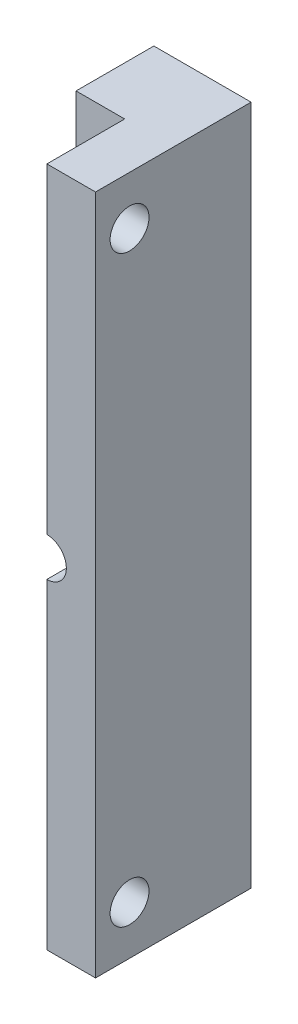
SolidWorks part; units mm, degrees
ref_plane "Front Plane" through (0, 0, 0) normal (0, 0, 1) x (1, 0, 0)
ref_plane "Top Plane" through (0, 0, 0) normal (0, 1, 0) x (1, 0, 0)
ref_plane "Right Plane" through (0, 0, 0) normal (1, 0, 0) x (0, 0, -1)
other "Configuration Table"
sketch "草图1" plane through (0, 0, 0) normal (0, 0, 1) x (1, 0, 0)
  line L0 (-15, 22) -> (-15, -22)
  line L1 (0, 22) -> (15, 22)
  line L2 (0, 22) -> (-15, 22)
  line L3 (15, 22) -> (15, -22)
  line L4 (15, -22) -> (-15, -22)
extrude "凸台-拉伸1" add sketch "草图1" along normal blind 14 contours L0 L4 L3 L1 L2
sketch "草图2" plane through (0, 22, 0) normal (0, 1, 0) x (1, 0, 0)
  line L3 (10, -4) -> (15, -14)
  line L4 (15, -14) -> (-15, -14)
  line L6 (-15, -14) -> (-10, -4)
  line L8 (3.1, -4) -> (3.1, 0)
  line L9 (-15, 0) -> (15, 0) construction
  line L10 (3.1, 0) -> (15, 0)
  line L11 (15, 0) -> (15, -14)
  line L12 (10, -4) -> (3.1, -4)
  line L13 (-3.1, -4) -> (-10, -4)
  line L14 (-15, -14) -> (-15, 0)
  line L15 (-15, 0) -> (-3.1, 0)
  line L16 (-3.1, 0) -> (-3.1, -4)
  line M14 (15, 0) -> (-15, 0)
  line M15 (-15, 0) -> (-15, -14)
  line M17 (15, -14) -> (15, 0)
extrude "切除-拉伸1" cut sketch "草图2" against normal blind 44 contours L16 L6 L13 M14 M15 | L12 L3 L8 M17 M14
sketch "草图3" plane through (0, 0, 0) normal (0, 0, -1) x (-1, 0, 0)
  line L2 (-3.1, 3.1) -> (-3.1, -3.1)
  line L4 (3.1, -22) -> (3.1, 22) construction
  line L5 (3.1, 3.1) -> (-3.1, 3.1)
  line L6 (-3.1, -22) -> (-3.1, 22) construction
  line L9 (-3.1, -3.1) -> (3.1, -3.1)
  line L10 (3.1, -22) -> (3.1, 22) construction
  line L11 (3.1, -3.1) -> (3.1, 3.1)
extrude "切除-拉伸2" cut sketch "草图3" against normal blind 4 contours L2 L9 L11 L5
sketch "草图4" plane through (0, 0, 14) normal (0, 0, 1) x (1, 0, 0)
  circle A0 centre (0, 0) radius 4
extrude "切除-拉伸3" cut sketch "草图4" against normal blind 5
sketch "草图5" plane through (0, 0, 9) normal (0, 0, 1) x (1, 0, 0)
  circle A0 centre (0, 0) radius 2.6
extrude "切除-拉伸4" cut sketch "草图5" against normal blind 5 contours A0
sketch "草图6" plane through (0, 0, 4) normal (0, 0, -1) x (-1, 0, 0)
  line L1 (10, 22) -> (15, 22)
  line L2 (10, 22) -> (10, -22)
  line L3 (10, -22) -> (15, -22)
  line L4 (15, 22) -> (15, -22)
extrude "切除-拉伸5" cut sketch "草图6" against normal blind 10 contours L2 L1 L4 L3
sketch "草图7" plane through (0, 0, 4) normal (0, 0, -1) x (-1, 0, 0)
  line L1 (-10, 22) -> (-15, 22)
  line L2 (-10, 22) -> (-10, -22)
  line L3 (-10, -22) -> (-15, -22)
  line L4 (-15, 22) -> (-15, -22)
extrude "切除-拉伸6" cut sketch "草图7" against normal blind 10 contours L2 L1 L4 L3
sketch "草图9" plane through (0, 22, 0) normal (0, 1, 0) x (1, 0, 0)
  line L0 (-3.1, 0) -> (3.1, 0)
  line L1 (3.1, 0) -> (3.1, -4)
  line L2 (3.1, -4) -> (10, -4)
  line L3 (10, -4) -> (10, -14)
  line L4 (10, -14) -> (-10, -14)
  line L5 (-10, -14) -> (-10, -4)
  line L6 (-10, -4) -> (-3.1, -4)
  line L7 (-3.1, -4) -> (-3.1, 0)
extrude "凸台-拉伸3" add sketch "草图9" along normal blind 48 contours L7 L0 L1 L2 L3 L4 L5 L6
sketch "草图10" plane through (0, -22, 0) normal (0, -1, 0) x (-1, 0, 0)
  line L0 (10, -14) -> (-10, -14)
  line L1 (-10, -14) -> (-10, -4)
  line L2 (-10, -4) -> (-3.1, -4)
  line L3 (-3.1, -4) -> (-3.1, 0)
  line L4 (-3.1, 0) -> (3.1, 0)
  line L5 (3.1, 0) -> (3.1, -4)
  line L6 (3.1, -4) -> (10, -4)
  line L7 (10, -4) -> (10, -14)
extrude "凸台-拉伸4" add sketch "草图10" along normal blind 48 contours L7 L0 L1 L2 L3 L4 L5 L6
sketch "草图11" plane through (10, 0, 0) normal (1, 0, 0) x (0, 0, -1)
  line L1 (-14, 70) -> (-36, 70)
  line L2 (-14, 70) -> (-14, -70)
  line L3 (-14, -70) -> (-36, -70)
  line L4 (-36, 70) -> (-36, -70)
extrude "凸台-拉伸5" add sketch "草图11" against normal blind 20 contours L2 L1 L4 L3
sketch "草图12" plane through (10, 0, 0) normal (1, 0, 0) x (0, 0, -1)
  line L0 (-4, 70) -> (-29, 70)
  line L1 (-4, 70) -> (-36, 70) construction
  line L2 (-29, 70) -> (-29, 60)
  line L3 (-4, -70) -> (-29, -70)
  line L4 (-36, -70) -> (-4, -70) construction
  line L5 (-29, -70) -> (-29, -60)
  circle A0 centre (-29, 60) radius 4
  circle A1 centre (-29, -60) radius 4
extrude "切除-拉伸7" cut sketch "草图12" against normal blind 20
sketch "草图13" plane through (0, -70, 0) normal (0, -1, 0) x (1, 0, 0)
  line L0 (-10, 36) -> (-10, 4)
  line L1 (-10, 20) -> (0, 20)
  line L2 (0, 20) -> (0, 36)
  line L3 (-10, 36) -> (10, 36) construction
  line L4 (0, 36) -> (-10, 36)
  line M7 (10, 36) -> (-10, 36)
  line M8 (-10, 36) -> (-10, 4)
extrude "切除-拉伸8" cut sketch "草图13" against normal blind 140 contours L1 L2 M7 M8
sketch "草图14" plane through (0, 0, 20) normal (0, 0, 1) x (1, 0, 0)
  line L0 (0, 70) -> (0, -70)
  circle A0 centre (0, 0) radius 4
extrude "切除-拉伸9" cut sketch "草图14" against normal blind 6 contours L0 A0 | L0 A0
sketch "草图15" plane through (0, 0, 36) normal (0, 0, 1) x (1, 0, 0)
  line L0 (0, 70) -> (0, -70) construction
  circle A0 centre (0, 0) radius 4
extrude "切除-拉伸10" cut sketch "草图15" against normal blind 20 contours A0
sketch "草图16" plane through (0, 0, 0) normal (0, 0, -1) x (-1, 0, 0)
  line L0 (3.1, 3.1) -> (3.1, 70) construction
  line L1 (-3.1, 70) -> (3.1, 70)
  line L2 (-3.1, 70) -> (-3.1, 48)
  line L3 (-3.1, 48) -> (3.1, 48)
  line L4 (3.1, 70) -> (3.1, 48)
  line L6 (3.1, -70) -> (-3.1, -70)
  line L7 (3.1, -70) -> (3.1, -48)
  line L8 (3.1, -48) -> (-3.1, -48)
  line L9 (-3.1, -70) -> (-3.1, -48)
extrude "切除-拉伸11" cut sketch "草图16" against normal blind 4 contours L2 L1 L4 L3 | L7 L6 L9 L8
